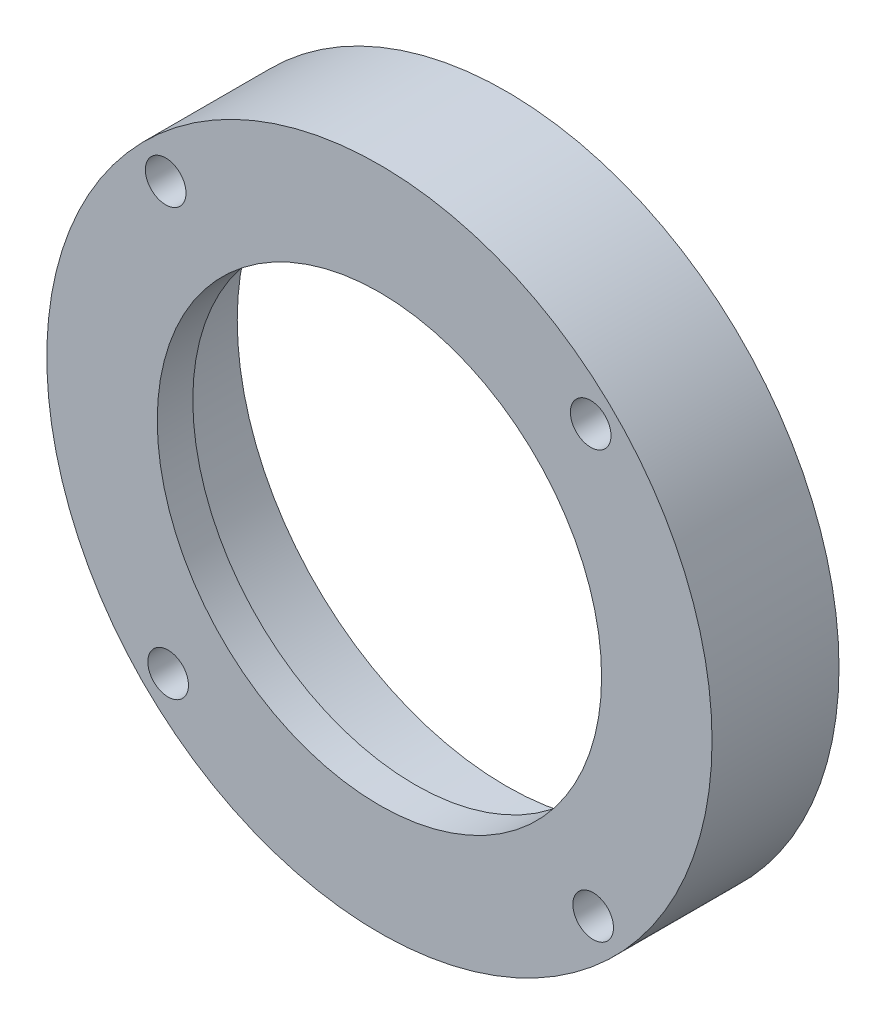
SolidWorks part; units mm, degrees
ref_plane "Front Plane" through (0, 0, 0) normal (0, 0, 1) x (1, 0, 0)
ref_plane "Top Plane" through (0, 0, 0) normal (0, 1, 0) x (1, 0, 0)
ref_plane "Right Plane" through (0, 0, 0) normal (1, 0, 0) x (0, 0, -1)
sketch "Sketch1" plane through (0, 0, 0) normal (0, 0, 1) x (1, 0, 0)
  circle A0 centre (0, 0) radius 26.2
  circle A1 centre (16.6413, 16.8357) radius 1.6 construction
  circle A2 centre (16.8355, -16.6417) radius 1.6 construction
  circle A3 centre (-16.6419, -16.836) radius 1.6 construction
  circle A4 centre (-16.8361, 16.6414) radius 1.6 construction
  circle A5 centre (16.6413, 16.8357) radius 1.6
  circle A6 centre (16.8355, -16.6417) radius 1.6
  circle A7 centre (-16.6419, -16.836) radius 1.6
  circle A8 centre (-16.8361, 16.6414) radius 1.6
  circle A9 centre (0, 0) radius 17.5
extrude "Boss-Extrude1" add sketch "Sketch1" along normal blind 10
sketch "Sketch2" plane through (0, 0, 0) normal (0, 0, -1) x (-1, 0, 0)
  circle A0 centre (0, 0) radius 21.2
extrude "Cut-Extrude1" cut sketch "Sketch2" against normal blind 7.2
